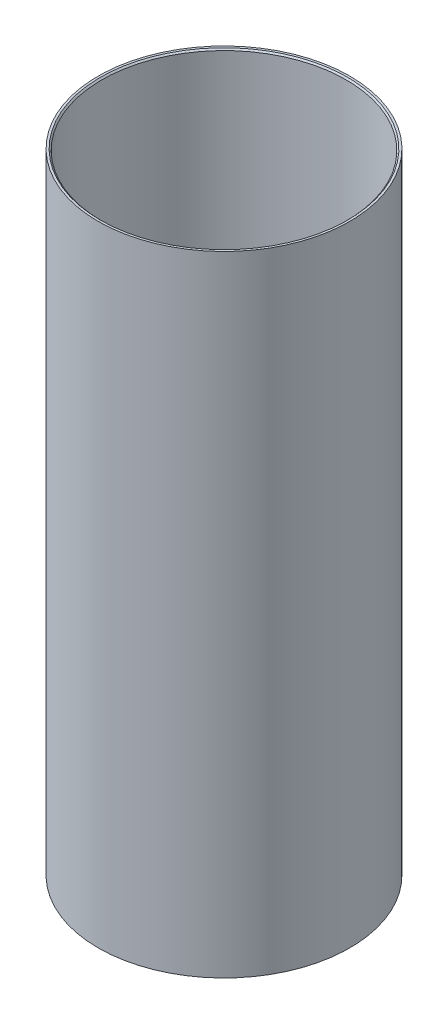
SolidWorks part; units mm, degrees
ref_plane "Front Plane" through (0, 0, 0) normal (0, 0, 1) x (1, 0, 0)
ref_plane "Top Plane" through (0, 0, 0) normal (0, 1, 0) x (1, 0, 0)
ref_plane "Right Plane" through (0, 0, 0) normal (1, 0, 0) x (0, 0, -1)
sketch "Sketch1" plane through (0, 0, 0) normal (0, 1, 0) x (1, 0, 0)
  circle A0 centre (0, 0) radius 17.5
  dimension "D1" = 35
extrude "Boss-Extrude1" add sketch "Sketch1" along normal blind 87.5
sketch "Sketch2" plane through (0, 87.5, 0) normal (0, 1, 0) x (1, 0, 0)
  circle A0 centre (0, 0) radius 17
  dimension "D1" = 34
extrude "Cut-Extrude1" cut sketch "Sketch2" against normal through all
chamfer "Chamfer1" distance 0.2 angle 45 2 edges at (0, 87.5, 17) (0, 0, 17)
